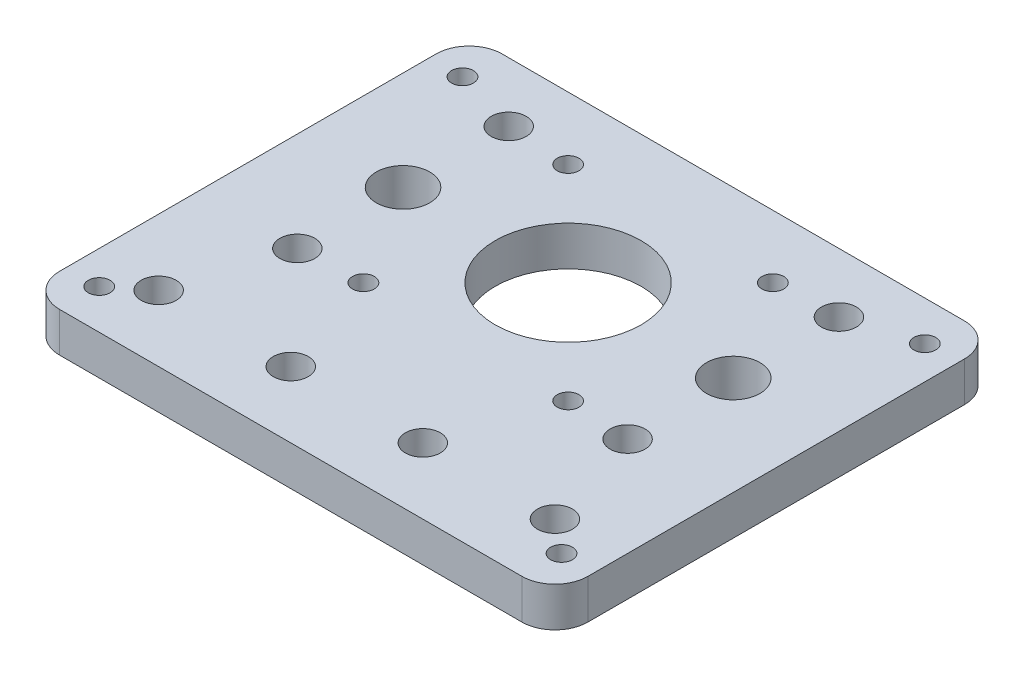
SolidWorks part; units mm, degrees
ref_plane "前视基准面" through (0, 0, 0) normal (0, 0, 1) x (1, 0, 0)
ref_plane "上视基准面" through (0, 0, 0) normal (0, 1, 0) x (1, 0, 0)
ref_plane "右视基准面" through (0, 0, 0) normal (1, 0, 0) x (0, 0, -1)
sketch "草图1" plane through (0, 0, 0) normal (0, 1, 0) x (1, 0, 0)
  line L0 (0, 80.3703) -> (0, -68.6055) construction
  line L1 (-122.6133, 0) -> (117.4549, 0) construction
  line L2 (-122.6133, -15.5) -> (117.4549, -15.5) construction
  line L3 (-15.5, 80.3703) -> (-15.5, -68.6055) construction
  line L4 (-122.6133, 15.5) -> (117.4549, 15.5) construction
  line L5 (15.5, 80.3703) -> (15.5, -68.6055) construction
  line L6 (-21.2, 80.3703) -> (-21.2, -68.6055) construction
  line L7 (21.2, 80.3703) -> (21.2, -68.6055) construction
  line L8 (-122.6133, -21.2) -> (117.4549, -21.2) construction
  line L9 (-122.6133, 21.2) -> (117.4549, 21.2) construction
  line L10 (-25, 80.3703) -> (-25, -68.6055) construction
  line L11 (25, 80.3703) -> (25, -68.6055) construction
  line L12 (-122.6133, -16) -> (117.4549, -16) construction
  line L13 (-122.6133, 16) -> (117.4549, 16) construction
  line L14 (-122.6133, -21.5) -> (117.4549, -21.5) construction
  line L15 (-122.6133, 21.5) -> (117.4549, 21.5) construction
  line L16 (-122.6133, -32) -> (117.4549, -32) construction
  line L17 (-122.6133, 32) -> (117.4549, 32) construction
  line L18 (-20, 80.3703) -> (-20, -68.6055) construction
  line L19 (20, 80.3703) -> (20, -68.6055) construction
  line L20 (-35, -42) -> (35, -42)
  line L21 (-122.6133, -22) -> (117.4549, -22) construction
  line L22 (-40, 20) -> (-40, -37)
  line L23 (40, 20) -> (40, -37)
  line L24 (-35, 25) -> (35, 25)
  line L25 (-40, 80.3703) -> (-40, -68.6055) construction
  line L26 (-122.6133, -42) -> (117.4549, -42) construction
  line L27 (40, 80.3703) -> (40, -68.6055) construction
  line L28 (-122.6133, 25) -> (117.4549, 25) construction
  line L29 (-35, 80.3703) -> (-35, -68.6055) construction
  circle A0 centre (0, 0) radius 11.05
  circle A3 centre (-15.5, 15.5) radius 1.65
  circle A4 centre (15.5, 15.5) radius 1.65
  circle A5 centre (15.5, -15.5) radius 1.65
  circle A6 centre (-15.5, -15.5) radius 1.65
  circle A7 centre (-25, 0) radius 4.05
  circle A8 centre (-25, 16) radius 2.65
  circle A9 centre (-25, -16) radius 2.65
  circle A10 centre (25, 0) radius 4.05
  circle A11 centre (25, -16) radius 2.65
  circle A12 centre (25, 16) radius 2.65
  arc A16 (-40, -37) -> (-35, -42) centre (-35, -37) ccw
  arc A17 (35, -42) -> (40, -37) centre (35, -37) ccw
  arc A18 (40, 20) -> (35, 25) centre (35, 20) ccw
  arc A19 (-35, 25) -> (-40, 20) centre (-35, 20) ccw
  circle A20 centre (-35, 19) radius 1.65
  circle A21 centre (-35, -36) radius 1.65
  circle A22 centre (35, -36) radius 1.65
  circle A23 centre (35, 19) radius 1.65
  circle A24 centre (-10, -32) radius 2.65
  circle A25 centre (-30, -32) radius 2.65
  circle A26 centre (30, -32) radius 2.65
  circle A27 centre (10, -32) radius 2.65
  point P26 (0, 0)
  dimension "D1" = 22.1
  dimension "D2" = 15.5
  dimension "D4" = 3.3
  dimension "D5" = 4
  dimension "D12" = 8.1
  dimension "D15" = 5.3
  dimension "D22" = 5.3
  dimension "D29" = 5
  dimension "D34" = 3.3
  dimension "D35" = 5.3
  dimension "D31" = 6
  dimension "D32" = 6
  dimension "D33" = 80
  dimension "D23" = 10
  dimension "D36" = 20
  dimension "D3" = 15.5
  dimension "D6" = 21.2
  dimension "D7" = 21.2
  dimension "D8" = 21.2
  dimension "D9" = 21.2
  dimension "D10" = 25
  dimension "D11" = 25
  dimension "D13" = 16
  dimension "D14" = 16
  dimension "D16" = 21.5
  dimension "D17" = 21.5
  dimension "D18" = 32
  dimension "D19" = 32
  dimension "D20" = 20
  dimension "D21" = 20
  dimension "D24" = 10
  dimension "D25" = 10
  dimension "D26" = 40
  dimension "D27" = 40
  dimension "D28" = 25
  dimension "D30" = 35
extrude "凸台-拉伸1" add sketch "草图1" along normal blind 6
